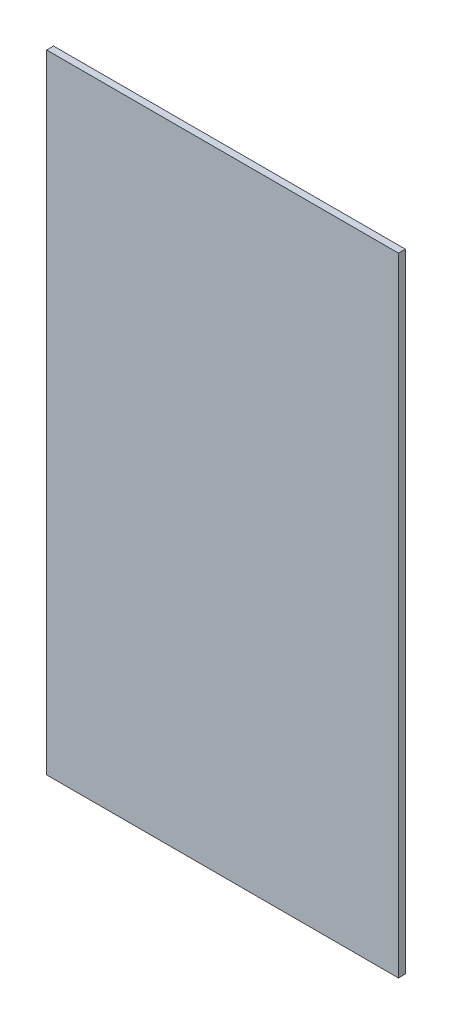
SolidWorks part; units mm, degrees
ref_plane "Front Plane" through (0, 0, 0) normal (0, 0, 1) x (1, 0, 0)
ref_plane "Top Plane" through (0, 0, 0) normal (0, 1, 0) x (1, 0, 0)
ref_plane "Right Plane" through (0, 0, 0) normal (1, 0, 0) x (0, 0, -1)
sketch "Sketch1" plane through (0, 0, 0) normal (0, 0, 1) x (1, 0, 0)
  line L8 (22.5, 477.5) -> (22.5, 22.5)
  line L9 (277.5, 477.5) -> (22.5, 477.5)
  line L10 (22.5, 22.5) -> (277.5, 22.5)
  line L11 (277.5, 22.5) -> (277.5, 477.5)
  line L12 (22.5, 477.5) -> (22.5, 22.5)
  line L13 (277.5, 477.5) -> (22.5, 477.5)
  line L14 (22.5, 22.5) -> (277.5, 22.5)
  line L15 (277.5, 22.5) -> (277.5, 477.5)
  dimension "D1" = 2.5
extrude "Boss-Extrude1" add sketch "Sketch1" against normal blind 5
